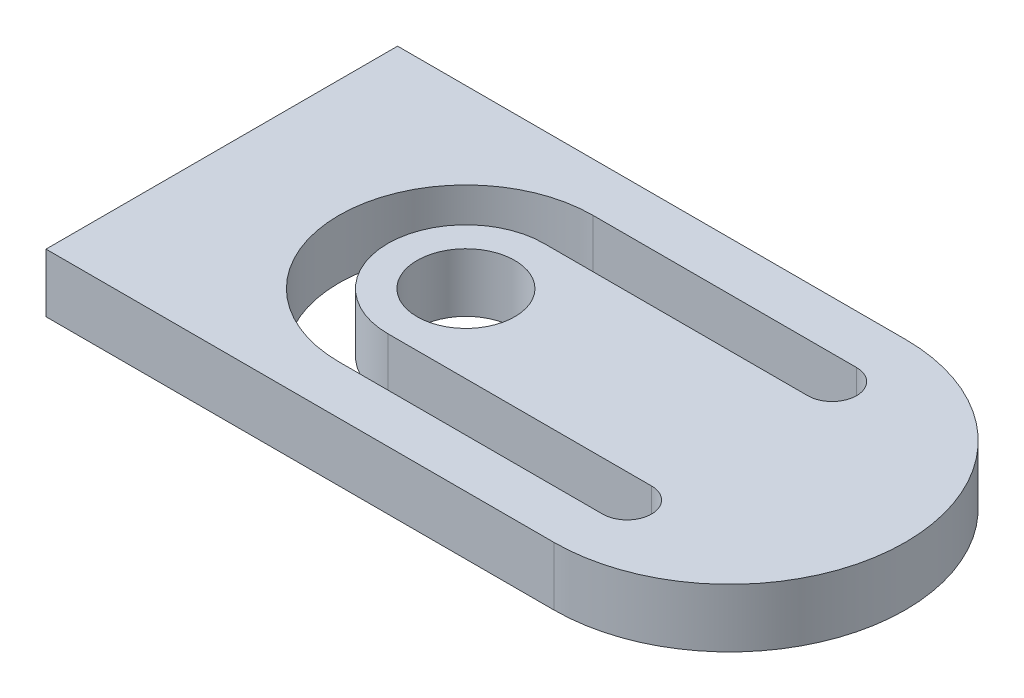
SolidWorks part; units mm, degrees
ref_plane "Front Plane" through (0, 0, 0) normal (0, 0, 1) x (1, 0, 0)
ref_plane "Top Plane" through (0, 0, 0) normal (0, 1, 0) x (1, 0, 0)
ref_plane "Right Plane" through (0, 0, 0) normal (1, 0, 0) x (0, 0, -1)
sketch "Sketch1" plane through (0, 0, 0) normal (0, 1, 0) x (1, 0, 0)
  line L1 (-19.356, 9) -> (6.644, 9)
  line L2 (-19.356, 9) -> (-19.356, -9)
  line L3 (-19.356, -9) -> (6.644, -9)
  line L10 (-6.856, -6.5) -> (6.644, -6.5)
  line L11 (-6.856, -4) -> (6.644, -4)
  line L12 (-6.856, 4) -> (6.644, 4)
  line L13 (-6.856, 6.5) -> (6.644, 6.5)
  circle A0 centre (-6.856, 0) radius 2.5
  arc A1 (6.644, 9) -> (6.644, -9) centre (6.644, 0) cw
  arc A6 (6.644, 6.5) -> (6.644, 4) centre (6.644, 5.25) cw
  arc A7 (6.644, -4) -> (6.644, -6.5) centre (6.644, -5.25) cw
  arc A8 (-6.856, 4) -> (-6.856, -4) centre (-6.856, 0) ccw
  arc A9 (-6.856, 6.5) -> (-6.856, -6.5) centre (-6.856, 0) ccw
  point P0 (0, 0)
  point P8 (-6.856, 0)
extrude "Boss-Extrude2" add sketch "Sketch1" along normal blind 3
